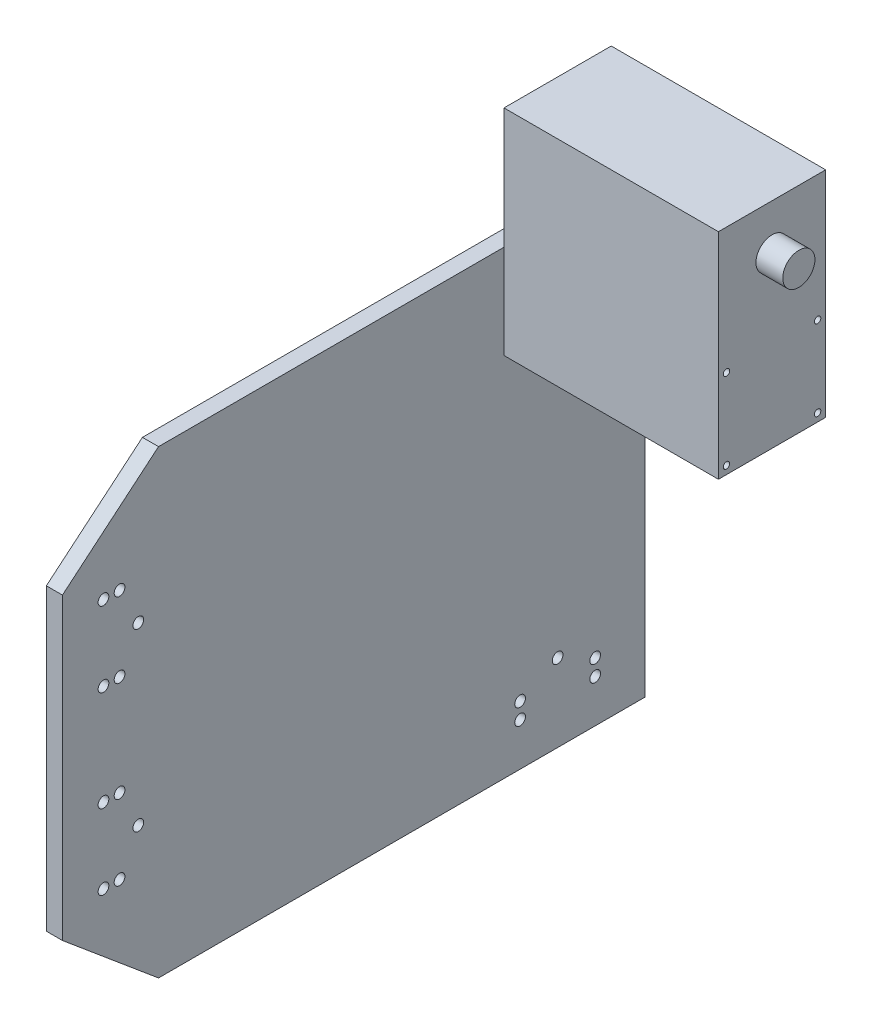
SolidWorks part; units mm, degrees
ref_plane "正面" through (0, 0, 0) normal (0, 0, 1) x (1, 0, 0)
ref_plane "平面" through (0, 0, 0) normal (0, 1, 0) x (1, 0, 0)
ref_plane "右側面" through (0, 0, 0) normal (1, 0, 0) x (0, 0, -1)
sketch "ｽｹｯﾁ1" plane through (0, 0, 0) normal (1, 0, 0) x (0, 0, -1)
  line L1 (8.409, 19.7991) -> (28.409, 19.7991)
  line L2 (8.409, 19.7991) -> (8.409, -20.2009)
  line L3 (8.409, -20.2009) -> (28.409, -20.2009)
  line L4 (28.409, 19.7991) -> (28.409, -20.2009)
extrude "ﾎﾞｽ - 押し出し1" add sketch "ｽｹｯﾁ1" along normal blind 40
sketch "ｽｹｯﾁ2" plane through (40, 0, 0) normal (1, 0, 0) x (0, 0, -1)
  line L1 (8.409, -20.2009) -> (28.409, -20.2009) construction
  line L2 (18.409, -20.2009) -> (18.409, -24.7228)
  circle A0 centre (26.909, -18.7009) radius 0.6
  circle A1 centre (26.909, -3.7009) radius 0.6
  circle A2 centre (9.909, -3.7009) radius 0.6
  circle A3 centre (9.909, -18.7009) radius 0.6
  point P13 (0, 0)
extrude "ｶｯﾄ - 押し出し1" cut sketch "ｽｹｯﾁ2" against normal blind 5 contours A0 | A1 | A2 | A3
sketch "ｽｹｯﾁ3" plane through (40, 0, 0) normal (1, 0, 0) x (0, 0, -1)
  line L0 (18.409, 19.7991) -> (18.409, 11.2991)
  line L1 (28.409, 19.7991) -> (8.409, 19.7991) construction
  circle A0 centre (18.409, 11.2991) radius 3
extrude "ﾎﾞｽ - 押し出し3" add sketch "ｽｹｯﾁ3" along normal blind 5 and the other way blind 45
sketch "ｽｹｯﾁ4" plane through (0, 0, 0) normal (-1, 0, 0) x (0, 0, 1)
  line L0 (-18.409, -17.2009) -> (-18.409, 3.417)
  circle A0 centre (-11.409, -13.7009) radius 1
  circle A1 centre (-11.409, -10.7009) radius 1
  circle A2 centre (-18.409, -17.2009) radius 1
  circle A3 centre (-25.409, -10.7009) radius 1
  circle A4 centre (-25.409, -13.7009) radius 1
  circle A5 centre (-10.409, 2.2991) radius 1
  circle A6 centre (-26.409, 2.2991) radius 1
  point P16 (0, 0)
extrude "ｶｯﾄ - 押し出し2" cut sketch "ｽｹｯﾁ4" against normal blind 5 contours A0 | A4 | A6 | A5 | A1 | A3 | A2
sketch "ｽｹｯﾁ5" plane through (0, 0, 0) normal (1, 0, 0) x (0, 0, -1)
  line L0 (34.7423, -2.6992) -> (-56.0386, -2.6992)
  line L1 (-56.0386, -2.6992) -> (-73.9631, -17.7178)
  line L2 (-73.9631, -17.7178) -> (-73.9631, -73.5239)
  line L4 (34.7423, -2.6992) -> (34.7423, -88.5425)
  line L5 (-56.0386, -88.5425) -> (-73.9631, -73.5239)
  line L6 (34.7423, -88.5425) -> (-56.0386, -88.5425)
  circle A0 centre (11.409, -10.7009) radius 1
  circle A1 centre (11.409, -13.7009) radius 1
  circle A2 centre (18.409, -17.2009) radius 1
  circle A3 centre (25.409, -10.7009) radius 1
  circle A4 centre (25.409, -13.7009) radius 1
  circle A5 centre (-66.3077, -36.256) radius 1
  circle A6 centre (-63.3077, -36.256) radius 1
  circle A7 centre (-59.8077, -29.256) radius 1
  circle A8 centre (-66.3077, -22.256) radius 1
  circle A9 centre (-63.3077, -22.256) radius 1
  circle A10 centre (25.409, -77.5408) radius 1
  circle A11 centre (25.409, -80.5408) radius 1
  circle A12 centre (18.409, -74.0408) radius 1
  circle A13 centre (11.409, -77.5408) radius 1
  circle A14 centre (11.409, -80.5408) radius 1
  circle A15 centre (-63.3077, -68.9857) radius 1
  circle A16 centre (-66.3077, -68.9857) radius 1
  circle A17 centre (-59.8077, -61.9857) radius 1
  circle A18 centre (-63.3077, -54.9857) radius 1
  circle A19 centre (-66.3077, -54.9857) radius 1
extrude "ﾎﾞｽ - 押し出し4" add sketch "ｽｹｯﾁ5" against normal blind 3
